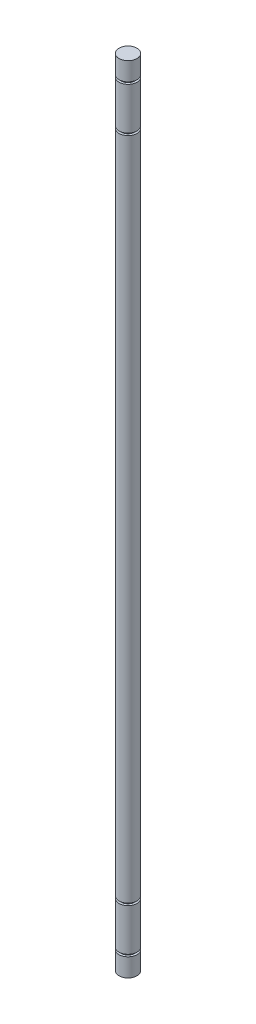
SolidWorks part; units mm, degrees
material "AISI 4130 Steel, annealed at 865C"
ref_plane "Front Plane" through (0, 0, 0) normal (0, 0, 1) x (1, 0, 0)
ref_plane "Top Plane" through (0, 0, 0) normal (0, 1, 0) x (1, 0, 0)
ref_plane "Right Plane" through (0, 0, 0) normal (1, 0, 0) x (0, 0, -1)
sketch "Sketch1" plane through (0, 0, 0) normal (0, 1, 0) x (1, 0, 0)
  circle A0 centre (0, 0) radius 1.5875
  dimension "D1" = 3.175
extrude "Boss-Extrude1" add sketch "Sketch1" along normal mid plane 140.1318
sketch "Sketch2" plane through (0, 0, 0) normal (0, 0, 1) x (1, 0, 0)
  line L1 (1.2065, 59.0042) -> (1.5875, 59.0042)
  line L2 (1.2065, 59.0042) -> (1.2065, 58.6232)
  line L3 (1.2065, 58.6232) -> (1.5875, 58.6232)
  line L4 (1.5875, 59.0042) -> (1.5875, 58.6232)
  line L5 (1.5875, -70.0659) -> (1.5875, 70.0659) construction
  line L6 (0, -58.6232) -> (0, 58.6232) construction
  line L7 (1.2065, -58.6232) -> (1.5875, -58.6232)
  line L8 (1.2065, -58.6232) -> (1.2065, -59.0042)
  line L9 (1.2065, -59.0042) -> (1.5875, -59.0042)
  line L10 (1.5875, -58.6232) -> (1.5875, -59.0042)
  line L11 (1.2065, 66.8274) -> (1.5875, 66.8274)
  line L12 (1.2065, 66.8274) -> (1.2065, 66.4464)
  line L13 (1.2065, 66.4464) -> (1.5875, 66.4464)
  line L14 (1.5875, 66.8274) -> (1.5875, 66.4464)
  line L15 (1.2065, -66.4464) -> (1.5875, -66.4464)
  line L16 (1.2065, -66.4464) -> (1.2065, -66.8274)
  line L17 (1.2065, -66.8274) -> (1.5875, -66.8274)
  line L18 (1.5875, -66.4464) -> (1.5875, -66.8274)
  point P4 (0, 0)
  point P5 (0, 0)
  point P20 (1.5875, -58.8137)
  point P21 (1.5875, -66.6369)
  point P22 (1.5875, 66.6369)
  point P23 (1.5875, 58.8137)
  point P26 (0, 0)
  point P28 (0, 0)
  point P29 (0, 0)
  point P30 (0, 0)
  point P31 (0, 0)
  dimension "D1" = 0.381
  dimension "D2" = 7.8232
  dimension "D3" = 7.8232
  dimension "D4" = 117.6274
  dimension "D5" = 1.2065
  dimension "D6" = 117.2464
revolve "Cut-Revolve1" cut sketch "Sketch2" angle 360 about L6
